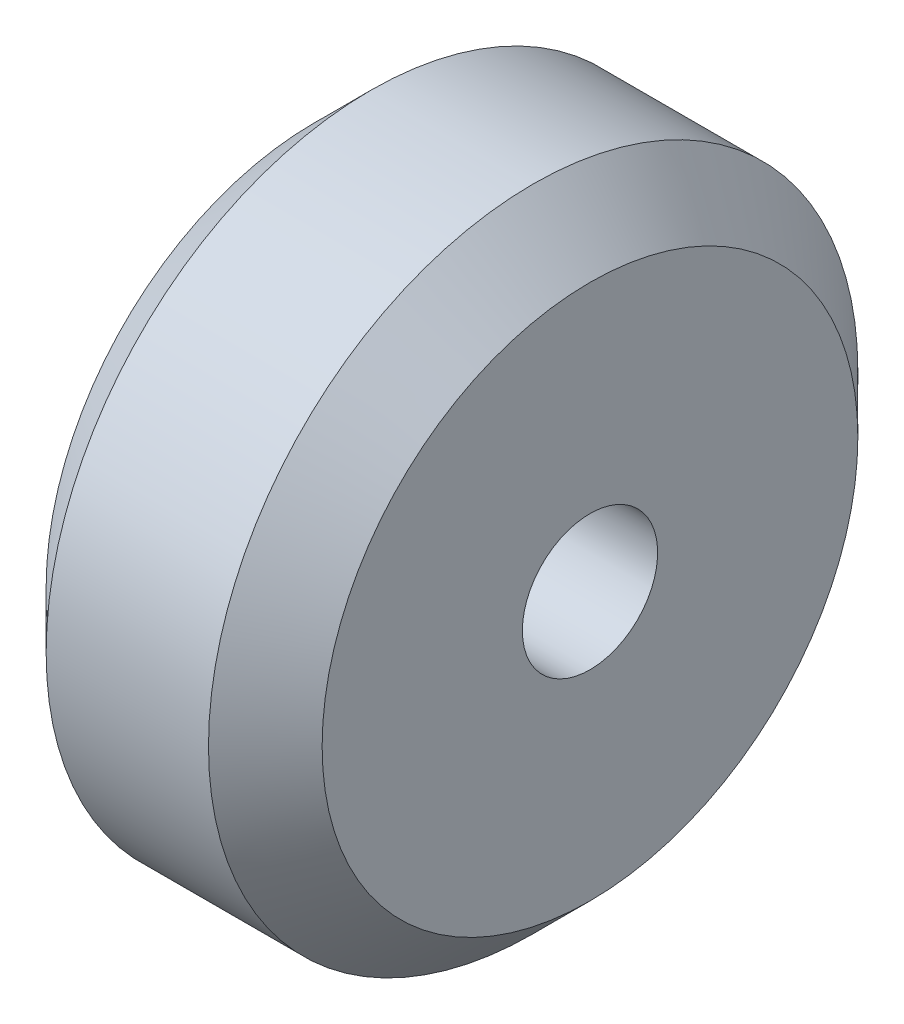
SolidWorks part; units mm, degrees
material "BUTYL"
ref_plane "Front Plane" through (0, 0, 0) normal (0, 0, 1) x (1, 0, 0)
ref_plane "Top Plane" through (0, 0, 0) normal (0, 1, 0) x (1, 0, 0)
ref_plane "Right Plane" through (0, 0, 0) normal (1, 0, 0) x (0, 0, -1)
sketch "Sketch1" plane through (0, 0, 0) normal (0, 1, 0) x (1, 0, 0)
  line L0 (0, 0) -> (24.5533, 0) construction
  line L1 (0, 0) -> (0, 2.5) construction
  line L2 (0, 2.5) -> (0, 9.9)
  line L3 (0, 9.9) -> (2.1, 12)
  line L4 (2.1, 12) -> (8.1, 12)
  line L5 (8.1, 12) -> (10.2, 9.9)
  line L6 (10.2, 9.9) -> (10.2, 2.5)
  line L7 (10.2, 2.5) -> (0, 2.5)
  line L8 (5.1, 2.5) -> (5.1, 12) construction
  dimension "D1" = 10.2
  dimension "D2" = 6
  dimension "D3" = 2.5
  dimension "D4" = 12
revolve "Revolve1" add sketch "Sketch1" angle 360 about L0
